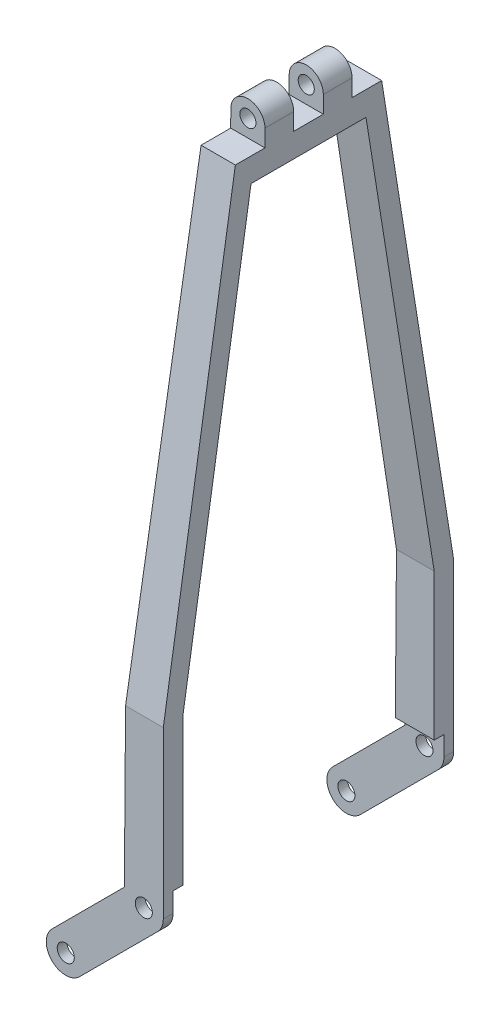
SolidWorks part; units mm, degrees
ref_plane "Front Plane" through (0, 0, 0) normal (0, 0, 1) x (1, 0, 0)
ref_plane "Top Plane" through (0, 0, 0) normal (0, 1, 0) x (1, 0, 0)
ref_plane "Right Plane" through (0, 0, 0) normal (1, 0, 0) x (0, 0, -1)
sketch "Croquis1" plane through (0, 0, 0) normal (0, 0, 1) x (1, 0, 0)
  line L0 (-13.1716, -18.8284) -> (2.8284, -2.8284)
  line L5 (-3.9873, 1.6696) -> (-18.8284, -13.1716)
  line L10 (-2.9999, 130.026) -> (-3.9873, 1.6696)
  line L11 (4, 0) -> (4, 129.999)
  circle A18 centre (0, 0) radius 1.75
  circle A19 centre (-16, -16) radius 1.75
  arc A20 (-18.8284, -13.1716) -> (-13.1716, -18.8284) centre (-16, -16) ccw
  arc A21 (2.8284, -2.8284) -> (4, 0) centre (0, 0) ccw
  arc A22 (4, 129.999) -> (-2.9999, 130.026) centre (0.5, 129.999) ccw
  circle A23 centre (0.5, 129.999) radius 1.65
  dimension "D3" = 3.5
  dimension "D4" = 8
  dimension "D6" = 7
  dimension "D7" = 3.3
  dimension "D1" = 16
  dimension "D2" = 16
  dimension "D5" = 130
extrude "Saliente-Extruir1" add sketch "Croquis1" against normal blind 59.54
sketch "Croquis2" plane through (4, 0, 0) normal (1, 0, 0) x (0, 0, -1)
  line L0 (0, -20) -> (59.54, -20) construction
  line L1 (2, -20) -> (57.54, -20)
  line L2 (2, -20) -> (2, 4)
  line L3 (2, 4) -> (57.54, 4)
  line L4 (57.54, -20) -> (57.54, 4)
  line L5 (59.54, 0) -> (0, 0) construction
  line L6 (14.77, 133.499) -> (0, 133.499)
  line L7 (0, 0) -> (0, 129.999) construction
  line L8 (4, 4) -> (55.54, 4)
  line L9 (4, 4) -> (4, 34)
  line L10 (4, 34) -> (55.54, 34)
  line L11 (55.54, 4) -> (55.54, 34)
  line L12 (59.54, 0) -> (59.54, 129.999) construction
  line L13 (29.77, 133.499) -> (29.77, 34) construction
  line L14 (55.54, 34) -> (41.5554, 121.5802)
  line L15 (0, 133.499) -> (0, 34)
  line L16 (59.54, 133.499) -> (0, 133.499) construction
  line L17 (59.54, 129.999) -> (0, 129.999) construction
  line L18 (59.54, 34) -> (59.54, 133.499)
  line L19 (59.54, 129.999) -> (59.54, 133.499) construction
  line L20 (59.54, 133.499) -> (44.77, 133.499)
  line L21 (44.77, 133.499) -> (44.77, 126.499)
  line L22 (44.77, 126.499) -> (59.54, 34)
  line L23 (0, 34) -> (14.77, 126.499)
  line L24 (14.77, 126.499) -> (14.77, 133.499)
  line L25 (0, 133.499) -> (0, 129.999) construction
  line L26 (4, 34) -> (17.9846, 121.5802)
  line L27 (17.9846, 121.5802) -> (41.5554, 121.5802)
  line L29 (14.77, 133.499) -> (20.84, 133.499)
  line L30 (14.77, 133.499) -> (14.77, 126.499)
  line L31 (14.77, 126.499) -> (20.84, 126.499)
  line L32 (20.84, 133.499) -> (20.84, 126.499)
  line L33 (44.77, 126.499) -> (38.7, 126.499)
  line L34 (44.77, 126.499) -> (44.77, 133.499)
  line L35 (44.77, 133.499) -> (38.7, 133.499)
  line L36 (38.7, 126.499) -> (38.7, 133.499)
  line L37 (32.805, 133.499) -> (26.735, 133.499)
  line L38 (32.805, 133.499) -> (32.805, 126.499)
  line L39 (32.805, 126.499) -> (26.735, 126.499)
  line L40 (26.735, 133.499) -> (26.735, 126.499)
  point P9 (29.77, 0)
  point P10 (29.77, 4)
  point P24 (29.77, 129.999)
  point P50 (29.77, 133.499)
  line M32 (0, 129.999) -> (0, 0)
  line M33 (0, 0) -> (59.54, 0)
  line M34 (59.54, 0) -> (59.54, 129.999)
  line M35 (59.54, 129.999) -> (0, 129.999)
  dimension "D1" = 55.54
  dimension "D2" = 30
  dimension "D3" = 4
  dimension "D4" = 4
  dimension "D5" = 15
  dimension "D6" = 7
  dimension "D7" = 4.9189
  dimension "D8" = 7
  dimension "D9" = 15
  dimension "D10" = 6.07
  dimension "D11" = 4
extrude "Cortar-Extruir1" cut sketch "Croquis2" against normal through all contours L32 L29 L24 M35 | L32 L24 L31 M35 | L36 L21 L35 M35 | L36 L33 L21 M35 | L20 L21 L18 M35 | L24 L6 L15 M35 | L23 L24 M35 M32 | L21 L22 M34 M35 | L3 L11 L10 L9 | L1 L4 L3 L2 M33 | L13 L27 L26 L10 | L27 L13 L10 L14 | L4 L3 L2 M33 | L39 L40 L37 L38
